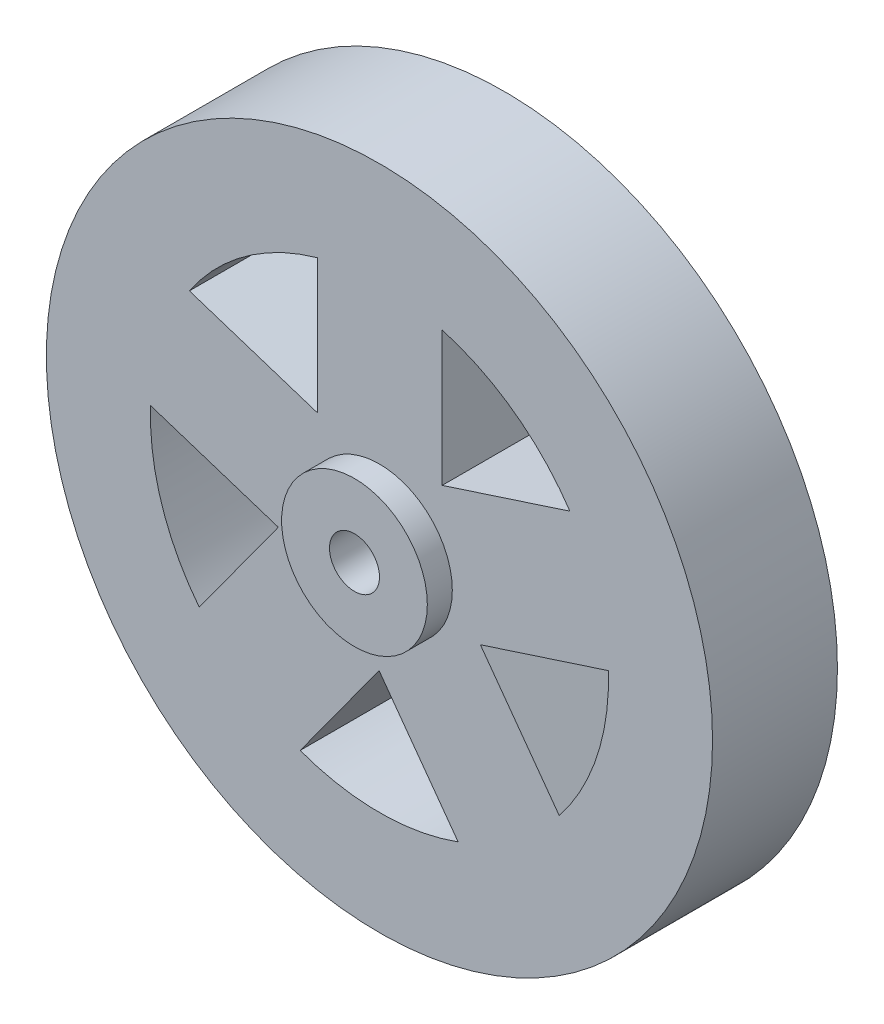
SolidWorks part; units mm, degrees
ref_plane "Front Plane" through (0, 0, 0) normal (0, 0, 1) x (1, 0, 0)
ref_plane "Top Plane" through (0, 0, 0) normal (0, 1, 0) x (1, 0, 0)
ref_plane "Right Plane" through (0, 0, 0) normal (1, 0, 0) x (0, 0, -1)
sketch "Sketch1" plane through (0, 0, 0) normal (0, 0, 1) x (1, 0, 0)
  circle A0 centre (0, 0) radius 40
  dimension "D1" = 80
extrude "Boss-Extrude1" add sketch "Sketch1" along normal blind 15
sketch "Sketch2" plane through (0, 0, 15) normal (0, 0, 1) x (1, 0, 0)
  circle A0 centre (0, 0) radius 27.5
  dimension "D1" = 55
extrude "Cut-Extrude1" cut sketch "Sketch2" against normal through all
sketch "Sketch3" plane through (0, 0, 0) normal (0, 0, 1) x (1, 0, 0)
  circle A0 centre (0, 0) radius 10
  dimension "D1" = 20
extrude "Boss-Extrude3" add sketch "Sketch3" along normal blind 15 separate body
sketch "Sketch5" plane through (0, 0, 0) normal (0, 1, 0) x (1, 0, 0)
  line L1 (-7.4627, 0) -> (7.5373, 0)
  line L2 (-7.4627, 0) -> (-7.4627, -15)
  line L3 (-7.4627, -15) -> (7.5373, -15)
  line L4 (7.5373, 0) -> (7.5373, -15)
  line L5 (-7.4627, 0) -> (7.5373, -15) construction
  line L6 (-7.4627, -15) -> (7.5373, 0) construction
  line L7 (10, 0) -> (-10, 0) construction
  point P0 (0.0373, -7.5)
  dimension "D1" = 15
  dimension "D3" = 15
extrude "Boss-Extrude4" add sketch "Sketch5" along normal up to surface (26.4469 mm away)
pattern_circular "CirPattern1" count 5 over 360 about axis through (0, 0, 0) along (0, 0, 1) of "Boss-Extrude4"
sketch "Sketch6" plane through (0, 0, 15) normal (0, 0, 1) x (1, 0, 0)
  circle A0 centre (0, 0) radius 8.75
  dimension "D1" = 17.5
extrude "Boss-Extrude5" add sketch "Sketch6" along normal blind 3
sketch "Sketch7" plane through (0, 0, 18) normal (0, 0, 1) x (1, 0, 0)
  circle A0 centre (0, 0) radius 3
  dimension "D1" = 6
extrude "Cut-Extrude2" cut sketch "Sketch7" against normal through all
